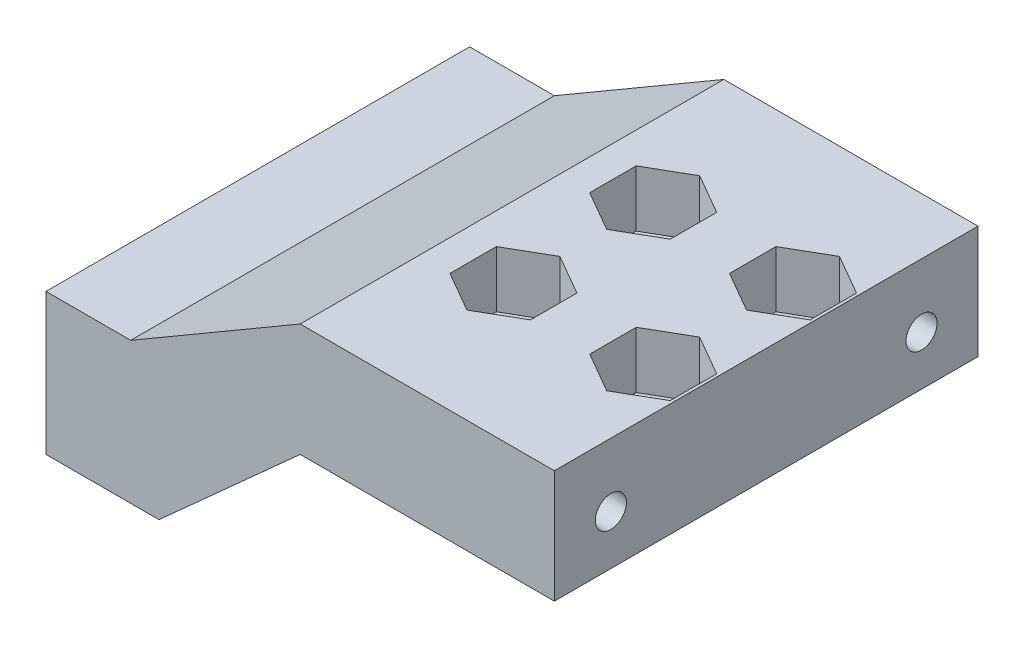
SolidWorks part; units mm, degrees
ref_plane "Спереди" through (0, 0, 0) normal (0, 0, 1) x (1, 0, 0)
ref_plane "Сверху" through (0, 0, 0) normal (0, 1, 0) x (1, 0, 0)
ref_plane "Справа" through (0, 0, 0) normal (1, 0, 0) x (0, 0, -1)
sketch "Эскиз1" plane through (0, 0, 0) normal (0, 1, 0) x (1, 0, 0)
  line L1 (0, 0) -> (41, 0)
  line L2 (0, 0) -> (0, 30)
  line L3 (0, 30) -> (41, 30)
  line L4 (41, 0) -> (41, 30)
  dimension "D1" = 41
  dimension "D2" = 30
extrude "Бобышка-Вытянуть1" add sketch "Эскиз1" along normal blind 10
sketch "Эскиз3" plane through (0, 0, 0) normal (-1, 0, 0) x (0, 0, 1)
  line L0 (-30, 10) -> (0, 10) construction
  line L1 (-30, 10) -> (0, 10)
  line L2 (-30, 10) -> (-30, 0)
  line L3 (-30, 0) -> (0, 0)
  line L4 (0, 10) -> (0, 0)
  line L5 (-30, 0) -> (0, 0) construction
  point P6 (-15, 10)
  point P9 (-15, 0)
  dimension "D1" = 10
  dimension "D2" = 30
extrude "Вырез-Вытянуть2" cut sketch "Эскиз3" against normal blind 3
sketch "Эскиз7" plane through (0, 0, -30) normal (0, 0, -1) x (-1, 0, 0)
  line L0 (-39, 10) -> (-39, 17) construction
  line L1 (-39, 17) -> (-21, 17)
  line L2 (-21, 17) -> (-9, 10)
  line L3 (-41, 10) -> (-3, 10) construction
  line L4 (-39, 10) -> (-9, 10)
  line L5 (-39, 17) -> (-39, 10)
  line L6 (-3, 10) -> (-3, 0) construction
  dimension "D1" = 12
  dimension "D2" = 18
  dimension "D3" = 18
  dimension "D4" = 7
extrude "Бобышка-Вытянуть3" add sketch "Эскиз7" against normal blind 30
sketch "Эскиз6" plane through (0, 0, 0) normal (0, -1, 0) x (1, 0, 0)
  line L0 (3, 0) -> (41, 0) construction
  line L1 (41, -30) -> (21, -30)
  line L2 (41, -30) -> (41, 0)
  line L3 (41, 0) -> (21, 0)
  line L4 (21, -30) -> (21, 0)
  dimension "D1" = 20
extrude "Вырез-Вытянуть5" cut sketch "Эскиз6" against normal blind 9
sketch "Эскиз2" plane through (39, 0, 0) normal (1, 0, 0) x (0, 0, -1)
  line L0 (0, 12.5) -> (30, 12.5) construction
  line L1 (0, 17) -> (30, 17) construction
  line L2 (0, 17) -> (0, 10) construction
  circle A0 centre (4, 12.5) radius 1.1
  circle A1 centre (26, 12.5) radius 1.1
  dimension "D1" = 2.2
  dimension "D3" = 4.5
  dimension "D4" = 22
  dimension "D5" = 4
extrude "Вырез-Вытянуть1" cut sketch "Эскиз2" against normal blind 15
sketch "Эскиз8" plane through (0, 9, 0) normal (0, 1, 0) x (1, 0, 0)
  line L0 (31, 15) -> (37.0104, 21.0104) construction
  line L1 (31, 15) -> (24.9896, 8.9896) construction
  line L2 (21, 0) -> (39, 0) construction
  line L3 (31, 15) -> (42.7004, 15) construction
  line L4 (24.9896, 21.0104) -> (37.0104, 8.9896) construction
  line L6 (21, 0) -> (21, 30) construction
  circle A0 centre (31, 15) radius 7 construction
  circle A1 centre (31, 15) radius 8.5 construction
  circle A2 centre (35.9497, 19.9497) radius 1.5
  circle A3 centre (35.9497, 10.0503) radius 1.5
  circle A4 centre (26.0503, 10.0503) radius 1.5
  circle A5 centre (26.0503, 19.9497) radius 1.5
  point P20 (31, 15)
  dimension "D1" = 14
  dimension "D2" = 17
  dimension "D6" = 4
  dimension "D3" = 10
  dimension "D4" = 15
  dimension "D5" = 45
extrude "Вырез-Вытянуть6" cut sketch "Эскиз8" along normal through all
sketch "Эскиз4" plane through (3, 0, 0) normal (-1, 0, 0) x (0, 0, 1)
  line L0 (-20, 5.4) -> (-8.9, 5.4) construction
  line L1 (0, 10) -> (-30, 10) construction
  line L2 (-20, 4.3) -> (-10, 4.3) construction
  circle A0 centre (-20, 5.4) radius 1.1
  circle A1 centre (-10, 5.4) radius 1.1
  point P5 (-15, 10)
  dimension "D1" = 5
  dimension "D2" = 2.2
  dimension "D3" = 10
  dimension "D4" = 4.6
extrude "Вырез-Вытянуть3" cut sketch "Эскиз4" against normal blind 10
sketch "Эскиз9" plane through (0, 0, -30) normal (0, 0, -1) x (-1, 0, 0)
  line L0 (-21, 9) -> (-21, 0)
  line L1 (-21, 9) -> (-21, 0) construction
  line L2 (-21, 0) -> (-11, 0)
  line L3 (-21, 0) -> (-3, 0) construction
  line L4 (-11, 0) -> (-21, 9)
  dimension "D1" = 10
extrude "Вырез-Вытянуть7" cut sketch "Эскиз9" against normal through all
sketch "Эскиз10" plane through (0, 17, 0) normal (0, 1, 0) x (1, 0, 0)
  line L1 (26.0503, 23.2406) -> (23.2003, 21.5952)
  line L2 (23.2003, 21.5952) -> (23.2003, 18.3043)
  line L3 (23.2003, 18.3043) -> (26.0503, 16.6589)
  line L4 (26.0503, 16.6589) -> (28.9003, 18.3043)
  line L5 (28.9003, 18.3043) -> (28.9003, 21.5952)
  line L6 (28.9003, 21.5952) -> (26.0503, 23.2406)
  line L7 (35.9497, 23.2406) -> (33.0997, 21.5952)
  line L8 (33.0997, 21.5952) -> (33.0997, 18.3043)
  line L9 (33.0997, 18.3043) -> (35.9497, 16.6589)
  line L10 (35.9497, 16.6589) -> (38.7997, 18.3043)
  line L11 (38.7997, 18.3043) -> (38.7997, 21.5952)
  line L12 (38.7997, 21.5952) -> (35.9497, 23.2406)
  line L13 (35.9497, 13.3411) -> (33.0997, 11.6957)
  line L14 (33.0997, 11.6957) -> (33.0997, 8.4048)
  line L15 (33.0997, 8.4048) -> (35.9497, 6.7594)
  line L16 (35.9497, 6.7594) -> (38.7997, 8.4048)
  line L17 (38.7997, 8.4048) -> (38.7997, 11.6957)
  line L18 (38.7997, 11.6957) -> (35.9497, 13.3411)
  line L19 (26.0503, 13.3411) -> (23.2003, 11.6957)
  line L20 (23.2003, 11.6957) -> (23.2003, 8.4048)
  line L21 (23.2003, 8.4048) -> (26.0503, 6.7594)
  line L22 (26.0503, 6.7594) -> (28.9003, 8.4048)
  line L23 (28.9003, 8.4048) -> (28.9003, 11.6957)
  line L24 (28.9003, 11.6957) -> (26.0503, 13.3411)
  circle A0 centre (26.0503, 19.9497) radius 2.85 construction
  circle A1 centre (35.9497, 19.9497) radius 2.85 construction
  circle A2 centre (35.9497, 10.0503) radius 2.85 construction
  circle A3 centre (26.0503, 10.0503) radius 2.85 construction
  dimension "D1" = 5.7
  dimension "D2" = 5.7
  dimension "D3" = 5.7
  dimension "D4" = 5.7
extrude "Вырез-Вытянуть8" cut sketch "Эскиз10" against normal blind 4
sketch "Эскиз11" plane through (0, 0, -30) normal (0, 0, -1) x (-1, 0, 0)
  line L1 (-39, 10) -> (-43.132, 10)
  line L2 (-39, 10) -> (-39, 6.7442)
  line L3 (-39, 6.7442) -> (-43.132, 6.7442)
  line L4 (-43.132, 10) -> (-43.132, 6.7442)
extrude "Вырез-Вытянуть9" cut sketch "Эскиз11" against normal through all
